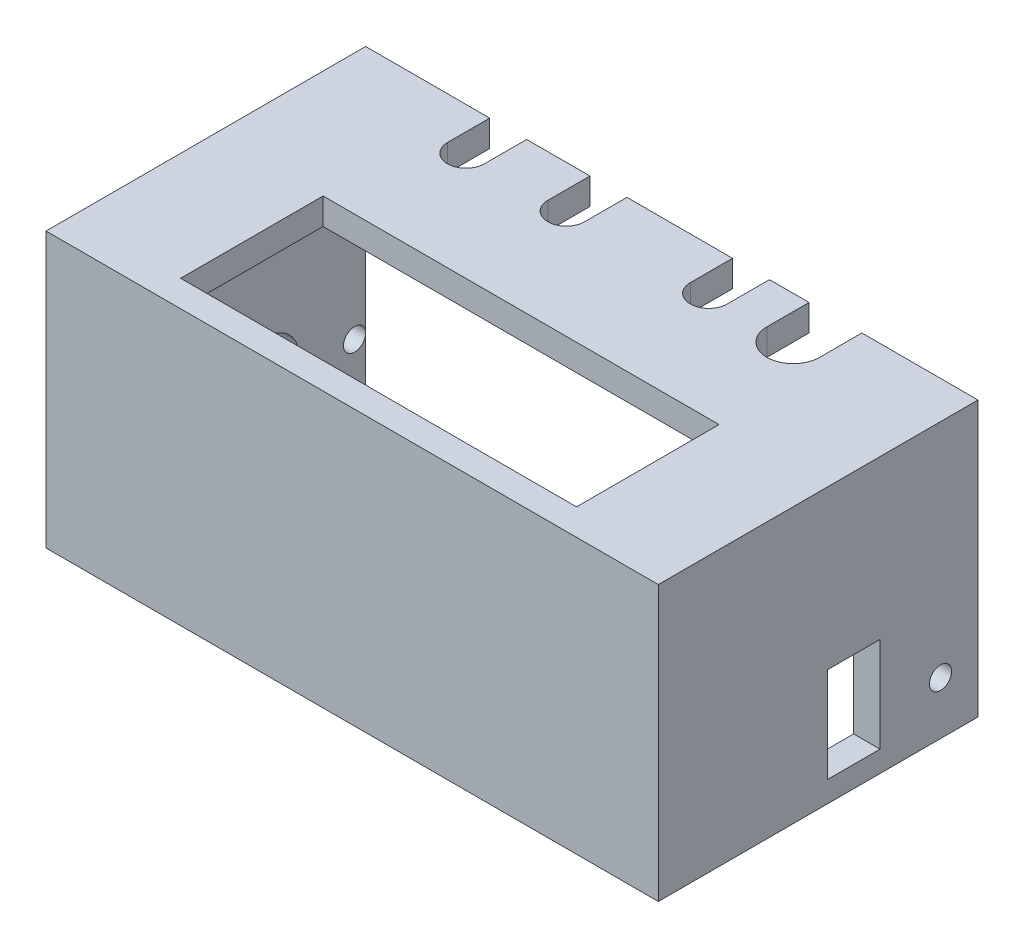
SolidWorks part; units mm, degrees
ref_plane "Ebene vorne" through (0, 0, 0) normal (0, 0, 1) x (1, 0, 0)
ref_plane "Ebene oben" through (0, 0, 0) normal (0, 1, 0) x (1, 0, 0)
ref_plane "Ebene rechts" through (0, 0, 0) normal (1, 0, 0) x (0, 0, -1)
sketch "Sketch1" plane through (0, 0, 0) normal (0, 1, 0) x (1, 0, 0)
  line L0 (-42.4437, 0) -> (42.4437, 0)
  line L1 (42.4437, 0) -> (58, 15.5563)
  line L2 (58, 15.5563) -> (58, -45)
  line L3 (58, -45) -> (-58, -45)
  line L4 (-58, -45) -> (-58, 15.5563)
  line L6 (-58, 15.5563) -> (-42.4437, 0)
  point P0 (-41.6057, 0)
  dimension "D1" = 116
  dimension "D2" = 116
  dimension "D3" = 22
  dimension "D4" = 22
  dimension "D5" = 45
  dimension "D6" = 58
  dimension "D7" = 0
  dimension "D8" = 45
extrude "Boss-Extrude1" add sketch "Sketch1" along normal blind 47
sketch "Sketch3" plane through (0, 0, 0) normal (0, 0, -1) x (-1, 0, 0)
  line L0 (-42.4437, 47) -> (-42.4437, 0) construction
  line L1 (-42.4437, 42) -> (42.4437, 42)
  line L2 (-42.4437, 42) -> (-42.4437, 0)
  line L3 (-42.4437, 0) -> (42.4437, 0)
  line L4 (42.4437, 42) -> (42.4437, 0)
  line L5 (0, 0) -> (0, 42) construction
  line L6 (-42.4437, 21) -> (42.4437, 21) construction
  line L7 (42.4437, 47) -> (42.4437, 0) construction
  line L8 (-42.4437, 0) -> (42.4437, 0) construction
  line L10 (-42.4437, 47) -> (42.4437, 47) construction
  point P0 (0, 21)
  dimension "D1" = 0
  dimension "D2" = 0
  dimension "D3" = 0
  dimension "D4" = 5
extrude "Cut-Extrude1" cut sketch "Sketch3" against normal offset from surface (40 mm away) 5 up to face at (0, 23.5, 45)
sketch "Sketch4" plane through (42.4437, 0, 0) normal (-1, 0, 0) x (0, 0, 1)
  line L0 (40, 42) -> (0, 42) construction
  line L1 (-15.5563, 42) -> (40, 42)
  line L2 (-15.5563, 42) -> (-15.5563, 0)
  line L3 (-15.5563, 0) -> (40, 0)
  line L4 (40, 42) -> (40, 0)
  line L5 (12.2218, 0) -> (12.2218, 42) construction
  line L6 (-15.5563, 21) -> (40, 21) construction
  line L7 (40, 0) -> (40, 42) construction
  line L8 (40, 0) -> (0, 0) construction
  line L9 (-15.5563, 47) -> (-15.5563, 0) construction
  point P0 (12.2218, 21)
  dimension "D1" = 0
  dimension "D2" = 0
  dimension "D3" = 0
  dimension "D4" = 0
extrude "Cut-Extrude2" cut sketch "Sketch4" against normal offset from surface (10.5563 mm away) 5 up to face at (58, 23.5, 14.7218)
sketch "Sketch5" plane through (-42.4437, 0, 0) normal (1, 0, 0) x (0, 0, -1)
  line L0 (-40, 42) -> (0, 42) construction
  line L1 (-40, 42) -> (15.5563, 42)
  line L2 (-40, 42) -> (-40, 0)
  line L3 (-40, 0) -> (15.5563, 0)
  line L4 (15.5563, 42) -> (15.5563, 0)
  line L5 (-12.2218, 0) -> (-12.2218, 42) construction
  line L6 (-40, 21) -> (15.5563, 21) construction
  line L7 (-40, 0) -> (0, 0) construction
  line L8 (-40, 42) -> (-40, 0) construction
  line L9 (15.5563, 47) -> (15.5563, 0) construction
  point P0 (-12.2218, 21)
  dimension "D1" = 0
  dimension "D2" = 0
  dimension "D3" = 0
  dimension "D4" = 0
extrude "Cut-Extrude3" cut sketch "Sketch5" against normal offset from surface (10.5563 mm away) 5 up to face at (-58, 23.5, 14.7218)
sketch "Sketch7" plane through (53, 0, 0) normal (-1, 0, 0) x (0, 0, 1)
  line L0 (45, 0) -> (-15.5563, 0) construction
  line L1 (3, 22) -> (13, 22)
  line L2 (3, 22) -> (3, 4)
  line L3 (3, 4) -> (13, 4)
  line L4 (13, 22) -> (13, 4)
  line L5 (8, 4) -> (8, 22) construction
  line L6 (3, 13) -> (13, 13) construction
  line L7 (0, 47) -> (0, 42) construction
  point P0 (8, 13)
  point P4 (8.4524, 12.3692)
  dimension "D1" = 18
  dimension "D2" = 10
  dimension "D3" = 4
  dimension "D4" = 3
extrude "Cut-Extrude5" cut sketch "Sketch7" against normal up to next
sketch "Sketch8" plane through (-58, 0, 0) normal (-1, 0, 0) x (0, 0, 1)
  circle A0 centre (8.5, 12.3015) radius 6.5
  dimension "D1" = 13
  dimension "D2" = 8.5
extrude "Cut-Extrude6" cut sketch "Sketch8" against normal up to next
sketch "Sketch10" plane through (0, 47, 0) normal (0, 1, 0) x (1, 0, 0)
  line L0 (58, -45) -> (-58, -45)
  line L1 (-58, -45) -> (-58, 15.5563)
  line L2 (-58, 15.5563) -> (-42.4437, 0)
  line L3 (-42.4437, 0) -> (42.4437, 0)
  line L4 (42.4437, 0) -> (58, 15.5563)
  line L5 (58, 15.5563) -> (58, -45)
extrude "Boss-Extrude2" add sketch "Sketch10" along normal blind 5
sketch "Sketch11" plane through (0, 0, 45) normal (0, 0, 1) x (1, 0, 0)
  line L0 (-58, 52) -> (58, 52) construction
  line L1 (-53, 47) -> (53, 47)
  line L2 (-53, 47) -> (-53, 0)
  line L3 (-53, 0) -> (53, 0)
  line L4 (53, 47) -> (53, 0)
  line L5 (0, 0) -> (0, 47) construction
  line L6 (-53, 23.5) -> (53, 23.5) construction
  line L7 (-58, 0) -> (58, 0) construction
  line L8 (53, 42) -> (53, 0) construction
  line L9 (-53, 0) -> (-53, 42) construction
  point P0 (0, 23.5)
  dimension "D1" = 5
  dimension "D2" = 0
  dimension "D3" = 0
  dimension "D4" = 0
extrude "Cut-Extrude7" cut sketch "Sketch11" against normal up to next from offset 5 offset against normal yes
sketch "Sketch12" plane through (0, 52, 0) normal (0, 1, 0) x (1, 0, 0)
  line L0 (58, 15.5563) -> (42.4437, 0)
  line L1 (42.4437, 0) -> (-42.4437, 0)
  line L2 (-42.4437, 0) -> (-58, 15.5563)
  line L3 (-58, 15.5563) -> (58, 15.5563)
extrude "Boss-Extrude3" add sketch "Sketch12" against normal blind 5
sketch "Sketch13" plane through (0, 52, 0) normal (0, 1, 0) x (1, 0, 0)
  line L0 (31, 7.5563) -> (31, 15.5563) construction
  line L1 (26, 7.5563) -> (26, 15.5563)
  line L2 (36, 7.5563) -> (36, 15.5563)
  line L3 (15, 7.5563) -> (15, 15.5563) construction
  line L4 (11.5, 7.5563) -> (11.5, 15.5563)
  line L5 (18.5, 7.5563) -> (18.5, 15.5563)
  line L6 (-12, 7.5563) -> (-12, 15.5563) construction
  line L7 (-15.5, 7.5563) -> (-15.5, 15.5563)
  line L8 (-8.5, 7.5563) -> (-8.5, 15.5563)
  line L9 (-31, 7.5563) -> (-31, 15.5563) construction
  line L10 (-34.5, 7.5563) -> (-34.5, 15.5563)
  line L11 (-27.5, 7.5563) -> (-27.5, 15.5563)
  line L12 (58, 15.5563) -> (-58, 15.5563) construction
  line L13 (-58, 15.5563) -> (-58, -45) construction
  arc A0 (26, 7.5563) -> (36, 7.5563) centre (31, 7.5563) ccw
  arc A1 (36, 15.5563) -> (26, 15.5563) centre (31, 15.5563) ccw
  arc A2 (11.5, 7.5563) -> (18.5, 7.5563) centre (15, 7.5563) ccw
  arc A3 (18.5, 15.5563) -> (11.5, 15.5563) centre (15, 15.5563) ccw
  arc A4 (-15.5, 7.5563) -> (-8.5, 7.5563) centre (-12, 7.5563) ccw
  arc A5 (-8.5, 15.5563) -> (-15.5, 15.5563) centre (-12, 15.5563) ccw
  arc A6 (-34.5, 7.5563) -> (-27.5, 7.5563) centre (-31, 7.5563) ccw
  arc A7 (-27.5, 15.5563) -> (-34.5, 15.5563) centre (-31, 15.5563) ccw
  point P2 (31, 11.5563)
  point P7 (15, 11.5563)
  point P14 (-12, 11.5563)
  point P21 (-31, 11.5563)
  point P32 (0, 0)
  dimension "D1" = 7
  dimension "D2" = 7
  dimension "D3" = 7
  dimension "D4" = 10
  dimension "D5" = 0
  dimension "D6" = 0
  dimension "D7" = 0
  dimension "D8" = 0
  dimension "D9" = 27
  dimension "D10" = 19
  dimension "D11" = 27
  dimension "D12" = 16
  dimension "D13" = 8
  dimension "D14" = 8
  dimension "D15" = 8
  dimension "D16" = 8
extrude "Cut-Extrude8" cut sketch "Sketch13" against normal up to next
sketch "Sketch14" plane through (0, 52, 0) normal (0, 1, 0) x (1, 0, 0)
  line L0 (-58, -45) -> (58, -45) construction
  line L1 (-37.5, -13) -> (37.5, -13)
  line L2 (-37.5, -13) -> (-37.5, -40)
  line L3 (-37.5, -40) -> (37.5, -40)
  line L4 (37.5, -13) -> (37.5, -40)
  line L5 (0, -40) -> (0, -13) construction
  line L6 (-37.5, -26.5) -> (37.5, -26.5) construction
  line L7 (-58, 15.5563) -> (-58, -45) construction
  point P0 (0, -26.5)
  dimension "D1" = 75
  dimension "D2" = 27
  dimension "D3" = 5
  dimension "D4" = 58
extrude "Cut-Extrude9" cut sketch "Sketch14" against normal up to next
sketch "Sketch16" plane through (58, 0, 0) normal (1, 0, 0) x (0, 0, -1)
  line L0 (15.5563, 47) -> (15.5563, 0) construction
  line L1 (-45, 0) -> (15.5563, 0) construction
  circle A0 centre (8.4563, 10) radius 2.1
  point P2 (0, 0)
  point P5 (0, 0)
  dimension "D1" = 4.2
  dimension "D2" = 7.1
  dimension "D3" = 10
extrude "Cut-Extrude10" cut sketch "Sketch16" against normal up to next and the other way through all
sketch "Sketch17" plane through (-58, 0, 0) normal (-1, 0, 0) x (0, 0, 1)
  line L0 (-15.5563, 47) -> (-15.5563, 0) construction
  line L1 (-15.5563, 0) -> (45, 0) construction
  circle A0 centre (-8.4563, 10) radius 2.1
  dimension "D1" = 4.2
  dimension "D2" = 7.1
  dimension "D3" = 10
extrude "Cut-Extrude11" cut sketch "Sketch17" against normal up to next
